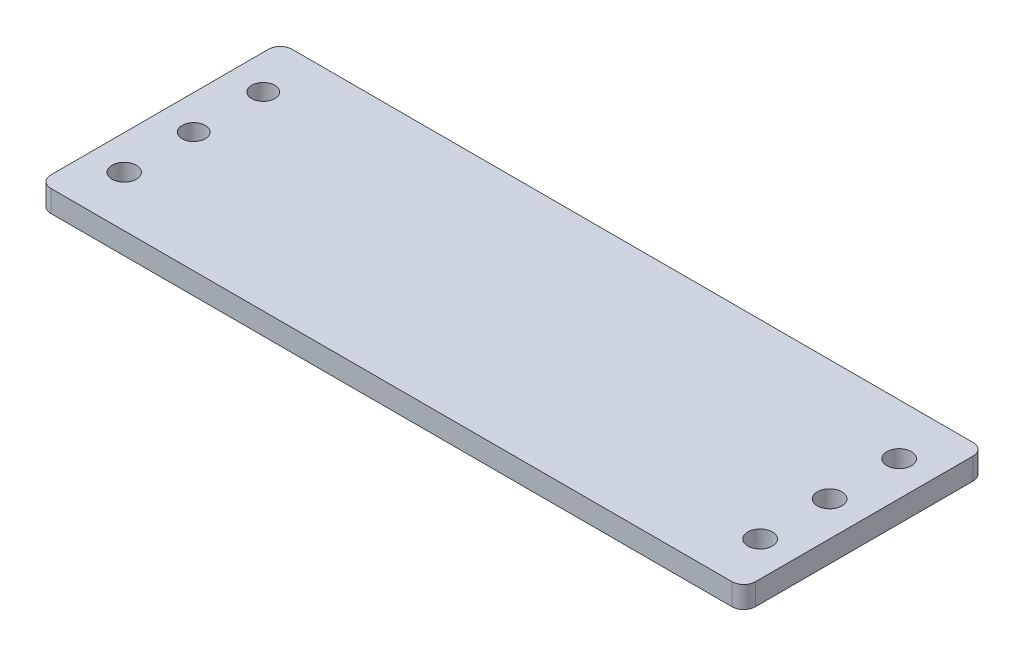
SolidWorks part; units mm, degrees
material "PE High Density Film"
ref_plane "Front Plane" through (0, 0, 0) normal (0, 0, 1) x (1, 0, 0)
ref_plane "Top Plane" through (0, 0, 0) normal (0, 1, 0) x (1, 0, 0)
ref_plane "Right Plane" through (0, 0, 0) normal (1, 0, 0) x (0, 0, -1)
sketch "Sketch1" plane through (0, 0, 0) normal (0, 1, 0) x (1, 0, 0)
  line L1 (-76.2, 26.416) -> (76.2, 26.416)
  line L2 (-76.2, 26.416) -> (-76.2, -26.416)
  line L3 (-76.2, -26.416) -> (76.2, -26.416)
  line L4 (76.2, 26.416) -> (76.2, -26.416)
  line L5 (-76.2, 26.416) -> (76.2, -26.416) construction
  line L6 (-76.2, -26.416) -> (76.2, 26.416) construction
  point P0 (0, 0)
  dimension "D1" = 152.4
  dimension "D2" = 52.832
extrude "Boss-Extrude1" add sketch "Sketch1" along normal blind 4.7625
sketch "Sketch2" plane through (0, 4.7625, 0) normal (0, 1, 0) x (1, 0, 0)
  line L0 (76.2, 26.416) -> (-76.2, 26.416) construction
  line L1 (74.957, 23.876) -> (74.957, -23.876) construction
  circle A0 centre (68.607, -15.24) radius 2.69
  circle A1 centre (68.607, 0) radius 2.69
  circle A2 centre (68.607, 15.24) radius 2.69
  dimension "D1" = 5.38
  dimension "D2" = 11.176
  dimension "D3" = 15.24
  dimension "D4" = 15.24
  dimension "D5" = 6.35
  dimension "D6" = 6.35
  dimension "D7" = 6.35
extrude "Cut-Extrude1" cut sketch "Sketch2" against normal through all
sketch "Sketch3" plane through (0, 4.7625, 0) normal (0, 1, 0) x (1, 0, 0)
  line L0 (0, -26.416) -> (0, 26.416) construction
  line L1 (-76.2, -26.416) -> (76.2, -26.416) construction
  line L2 (76.2, 26.416) -> (-76.2, 26.416) construction
sketch "Sketch5" plane through (0, 0, 0) normal (0, -1, 0) x (1, 0, 0)
  circle A0 centre (-70.6774, 15.3162) radius 2.667
  circle A1 centre (-70.6774, 0.0762) radius 2.54
  circle A2 centre (-70.6774, -15.1638) radius 2.54
  dimension "D1" = 5.334
extrude "Cut-Extrude2" cut sketch "Sketch5" against normal through all
sketch "Sketch6" plane through (-76.2, 0, 0) normal (-1, 0, 0) x (0, 0, 1)
  line L1 (26.416, 4.7625) -> (-26.416, 4.7625)
  line L2 (26.416, 4.7625) -> (26.416, 0)
  line L3 (26.416, 0) -> (-26.416, 0)
  line L4 (-26.416, 4.7625) -> (-26.416, 0)
extrude "Boss-Extrude2" add sketch "Sketch6" along normal blind 2
fillet "Fillet1" radius 2.54 4 edges at (76.2, 2.3813, 26.416) (76.2, 2.3813, -26.416) (-78.2, 2.3813, -26.416) (-78.2, 2.3813, 26.416)
